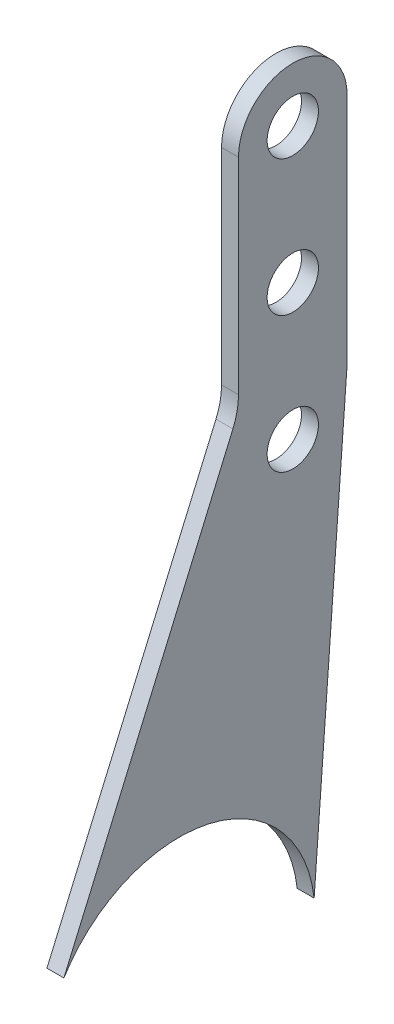
SolidWorks part; units mm, degrees
material "AISI 4130 Steel, annealed at 865C"
ref_plane "X-Y Datum" through (0, 0, 0) normal (0, 0, 1) x (1, 0, 0)
ref_plane "X-Z Datum" through (0, 0, 0) normal (0, 1, 0) x (1, 0, 0)
ref_plane "Y-Z Datum" through (0, 0, 0) normal (1, 0, 0) x (0, 0, -1)
sketch "Sketch1" plane through (0, 0, 0) normal (1, 0, 0) x (0, 0, -1)
  line L0 (0, -12.7) -> (0, 12.7) construction
  line L1 (-5.08, -6.5382) -> (-5.08, 12.7)
  line L2 (5.08, -8.9957) -> (5.08, 12.7)
  line L4 (0, -12.7) -> (-10.6172, -52.324) construction
  line L6 (-22.8845, -49.037) -> (1.65, -55.611) construction
  line L8 (-5.6013, -9.058) -> (-22.8845, -49.037)
  line L9 (5.0627, -9.464) -> (1.65, -55.611)
  line L10 (-18.5467, -39.0029) -> (2.7617, -40.5787) construction
  line L11 (-10.6172, -39.624) -> (0, -39.624) construction
  arc A0 (-5.08, 12.7) -> (5.08, 12.7) centre (0, 12.7) cw
  arc A2 (5.08, -8.9957) -> (5.0627, -9.464) centre (-1.27, -8.9957) cw
  arc A3 (-5.08, -6.5382) -> (-5.6013, -9.058) centre (-11.43, -6.5382) cw
  arc A4 (-22.8845, -49.037) -> (1.65, -55.611) centre (-10.6172, -52.324) cw
  point P12 (-10.6172, -52.324)
  point P13 (-1.27, -37.2329)
  point P16 (0, 0)
  point P21 (5.08, -7.3742)
  point P24 (-5.08, -7.3742)
  dimension "D2" = 5.08
  dimension "D3" = 15
  dimension "D4" = 25.4
  dimension "D6" = 6.35
  dimension "D1" = 25.4
  dimension "D5" = 26.924
extrude "Boss-Extrude1" add sketch "Sketch1" along normal mid plane 1.5875 contours L8 A4 L9 A2 L2 A0 L1 A3
hole_wizard "M4 Clearance Hole1" positions "Sketch2" profile "Sketch3" hole size "M4" standard "ANSI Metric" end condition up to next
sketch "Sketch2" plane through (0.7937, 0, 0) normal (1, 0, 0) x (0, 0, -1)
  point P0 (0, 0)
  point P3 (0, 12.7)
  point P6 (0, -12.7)
sketch "Sketch3" plane through (0.7937, 0, 0) normal (0, 1, 0) x (0, 0, -1)
  line L0 (0, 0) -> (0, 1.5875)
  line L1 (0, 1.5875) -> (2.4, 1.5875)
  line L2 (2.4, 1.5875) -> (2.4, 0)
  line L5 (2.4, 0) -> (0, 0)
  line L11 (0, -6.35) -> (0, 107.95) construction
  dimension "Thru Hole Dia." = 4.8
  dimension "Thru Hole Depth" = 1.5875
